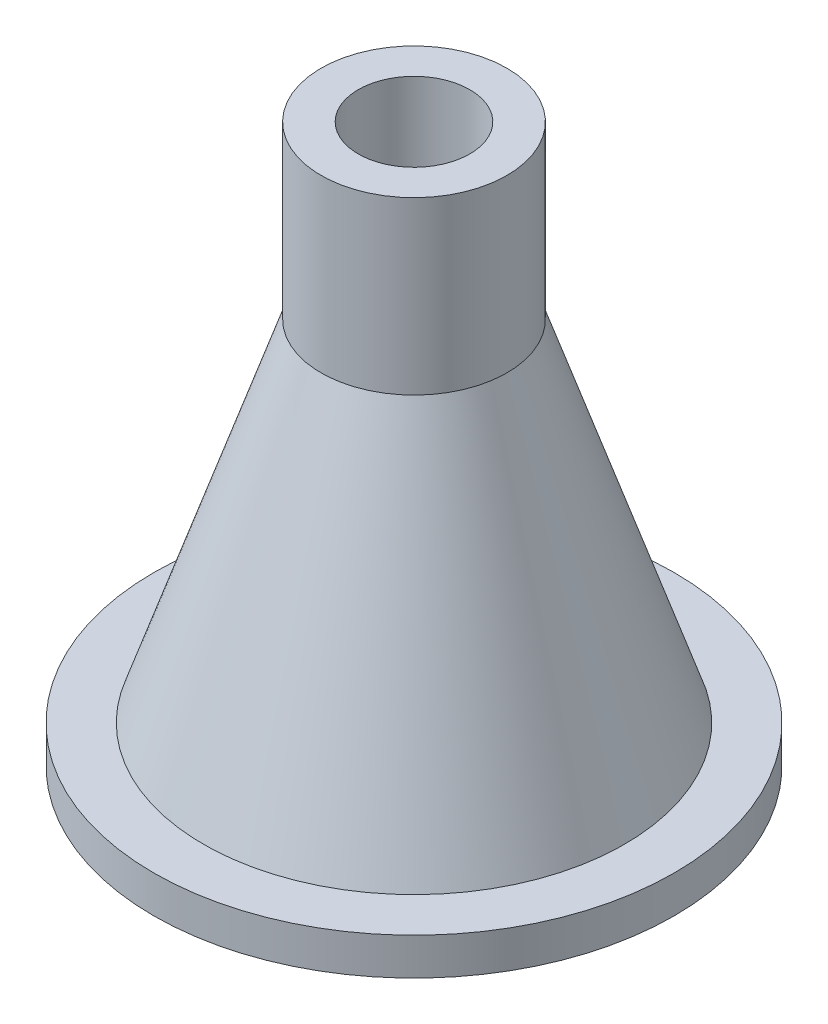
SolidWorks part; units mm, degrees
ref_plane "Front Plane" through (0, 0, 0) normal (0, 0, 1) x (1, 0, 0)
ref_plane "Top Plane" through (0, 0, 0) normal (0, 1, 0) x (1, 0, 0)
ref_plane "Right Plane" through (0, 0, 0) normal (1, 0, 0) x (0, 0, -1)
sketch "Sketch1" plane through (0, 0, 0) normal (0, 0, 1) x (1, 0, 0)
  line L9 (75, 750) -> (75, 520)
  line L10 (75, 520) -> (250, 0)
  line L11 (75, 750) -> (125, 750)
  line L12 (125, 750) -> (125, 520)
  line L13 (125, 520) -> (283.1731, 50)
  line L14 (283.1731, 50) -> (350, 50)
  line L15 (350, 50) -> (350, 0)
  line L16 (350, 0) -> (250, 0)
  line L17 (0, 0) -> (0, 1070.0625) construction
  point P0 (250, 0)
  point P1 (75, 750)
  dimension "D1" = 250
  dimension "D2" = 750
  dimension "D3" = 75
  dimension "D4" = 230
  dimension "D5" = 100
  dimension "D6" = 230
  dimension "D7" = 50
  dimension "D8" = 50
  dimension "D9" = 350
revolve "Revolve2" add sketch "Sketch1" angle 360 about L17
